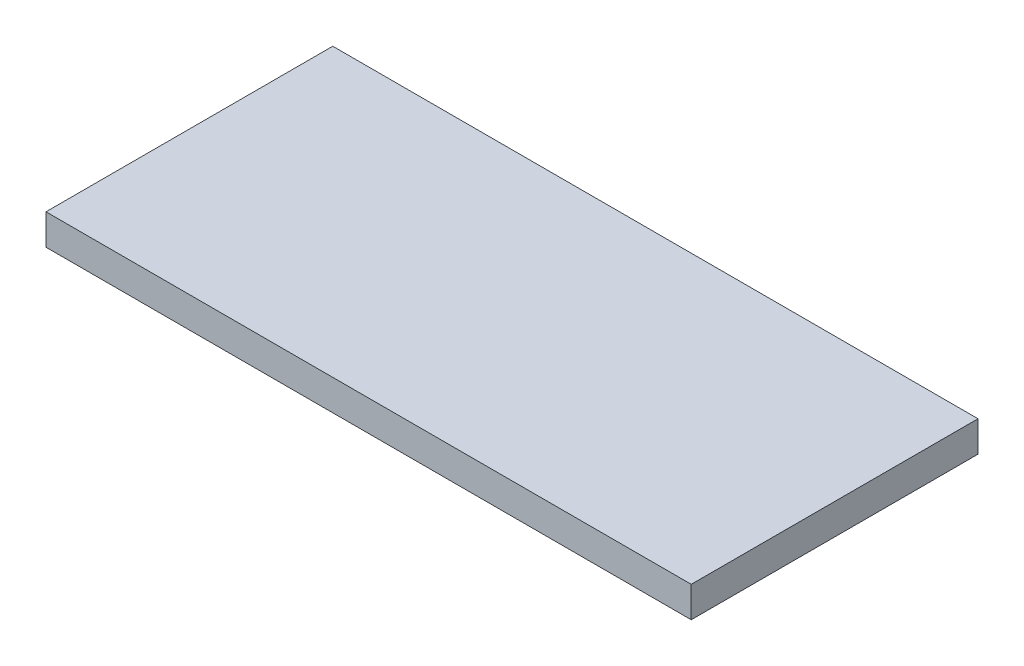
SolidWorks part; units mm, degrees
ref_plane "Front Plane" through (0, 0, 0) normal (0, 0, 1) x (1, 0, 0)
ref_plane "Top Plane" through (0, 0, 0) normal (0, 1, 0) x (1, 0, 0)
ref_plane "Right Plane" through (0, 0, 0) normal (1, 0, 0) x (0, 0, -1)
sketch "Sketch1" plane through (0, 0, 0) normal (0, 1, 0) x (1, 0, 0)
  line L1 (-28.1842, 19.7105) -> (34.8158, 19.7105)
  line L2 (-28.1842, 19.7105) -> (-28.1842, -8.2895)
  line L3 (-28.1842, -8.2895) -> (34.8158, -8.2895)
  line L4 (34.8158, 19.7105) -> (34.8158, -8.2895)
  dimension "D1" = 63
  dimension "D2" = 28
extrude "Boss-Extrude1" add sketch "Sketch1" along normal blind 3
